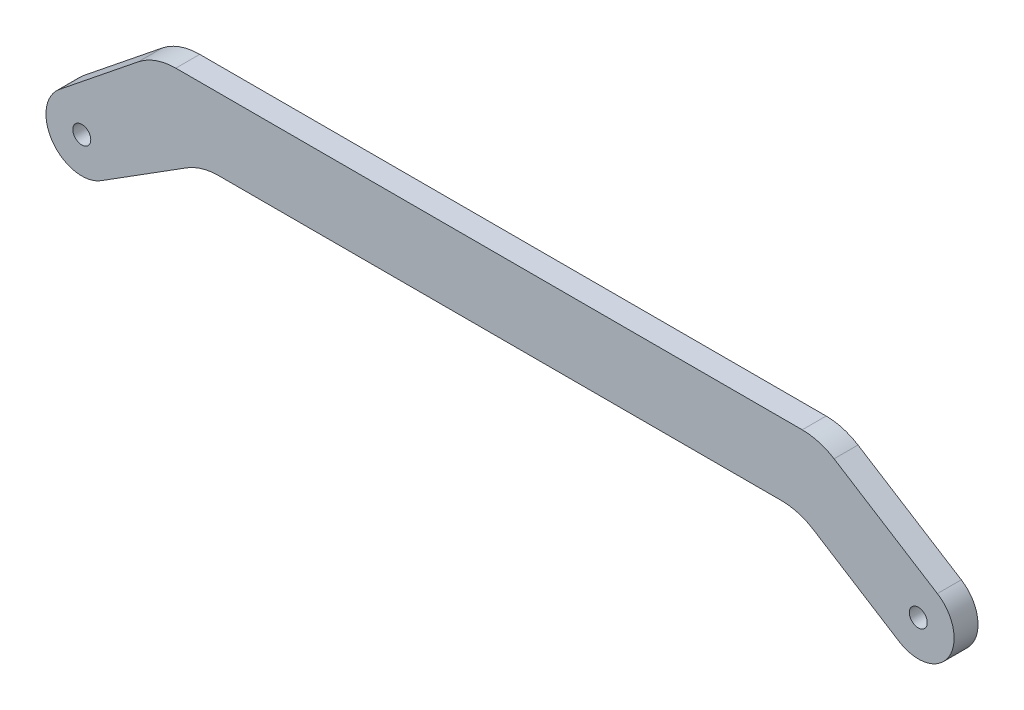
SolidWorks part; units mm, degrees
material "Acrílico (Impacto medio-alto)"
ref_plane "Piano frontale" through (0, 0, 0) normal (0, 0, 1) x (1, 0, 0)
ref_plane "Piano superiore" through (0, 0, 0) normal (0, 1, 0) x (1, 0, 0)
ref_plane "Piano destro" through (0, 0, 0) normal (1, 0, 0) x (0, 0, -1)
sketch "Schizzo1" plane through (0, 0, 0) normal (0, 0, 1) x (1, 0, 0)
  line L0 (0, 0) -> (1.5, 0) construction
  line L1 (0, 0) -> (1.5, 0) construction
  line L2 (-3.757, 4.6781) -> (9.4748, 15.3047)
  line L3 (15.7365, 17.5078) -> (120.5774, 17.5078)
  line L4 (122.4429, 3.9689) -> (136.8019, -5.0767)
  line L5 (125.9075, 15.9689) -> (143.1981, 5.0767)
  line L7 (17.5571, 3.9689) -> (3.1981, -5.0767)
  line L8 (22.8872, 5.5078) -> (117.1128, 5.5078)
  line L11 (0, 0) -> (138.5, 0) construction
  circle A0 centre (0, 0) radius 1.5
  circle A1 centre (140, 0) radius 1.5
  arc A2 (136.8019, -5.0767) -> (143.1981, 5.0767) centre (140, 0) ccw
  arc A3 (122.4429, 3.9689) -> (117.1128, 5.5078) centre (117.1128, -4.4922) ccw
  arc A4 (120.5774, 17.5078) -> (125.9075, 15.9689) centre (120.5774, 7.5078) cw
  arc A5 (-3.757, 4.6781) -> (3.1981, -5.0767) centre (0, 0) ccw
  arc A6 (17.5571, 3.9689) -> (22.8872, 5.5078) centre (22.8872, -4.4922) cw
  arc A7 (9.4748, 15.3047) -> (15.7365, 17.5078) centre (15.7365, 7.5078) cw
  point P10 (17.2528, 15)
  point P11 (20, 5.5078)
  point P15 (153.6285, 15)
  point P17 (120, 5.5078)
  point P18 (151.4002, 3)
  point P21 (123.4646, 17.5078)
  point P31 (12.2181, 17.5078)
  dimension "D1" = 3
  dimension "D2" = 3
  dimension "D4" = 12
  dimension "D5" = 12
  dimension "D8" = 20
  dimension "D10" = 10
  dimension "D3" = 140
  dimension "D7" = 12
  dimension "D6" = 20
  dimension "D9" = 111.2466
extrude "Estrusione-Estrusione1" add sketch "Schizzo1" along normal blind 4
